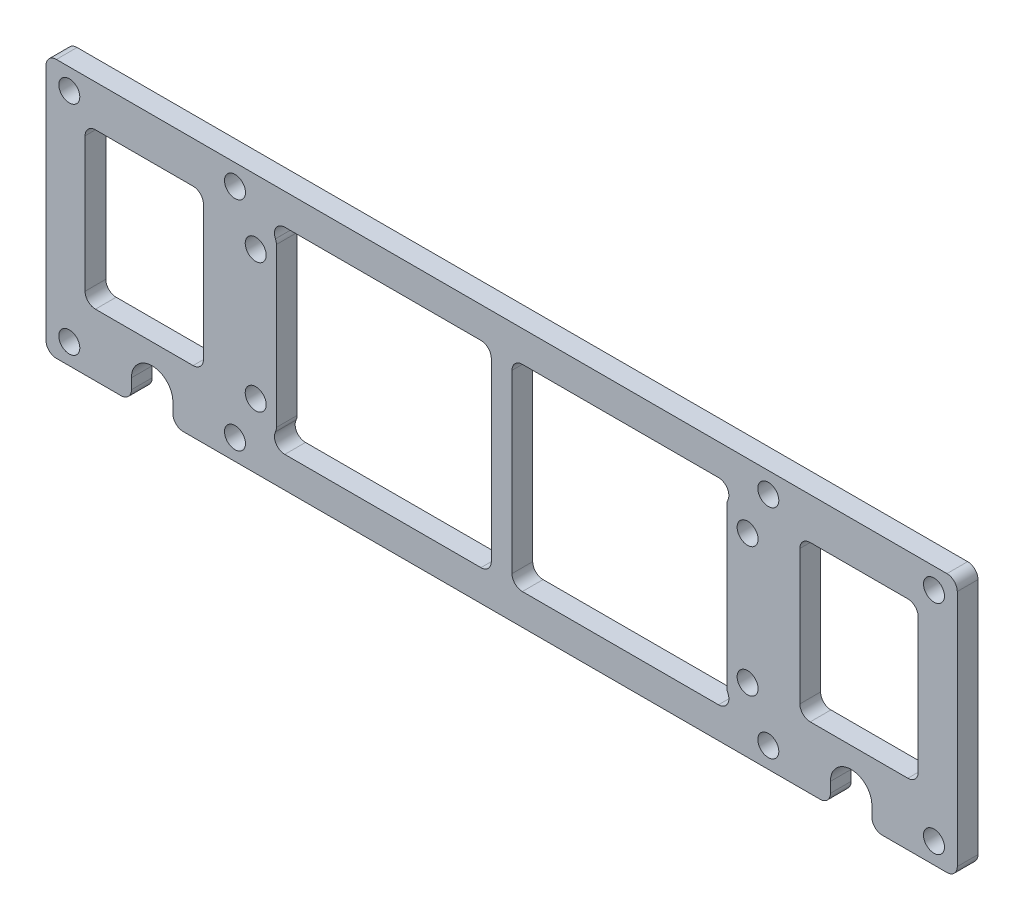
SolidWorks part; units mm, degrees
material "Thornel Mat VMA"
ref_plane "前视基准面" through (0, 0, 0) normal (0, 0, 1) x (1, 0, 0)
ref_plane "上视基准面" through (0, 0, 0) normal (0, 1, 0) x (1, 0, 0)
ref_plane "右视基准面" through (0, 0, 0) normal (1, 0, 0) x (0, 0, -1)
other "Configuration Table"
sketch "草图1" plane through (0, 0, 0) normal (0, 0, 1) x (1, 0, 0)
  line L1 (-88, -25) -> (88, -25)
  line L2 (-88, -25) -> (-88, 25)
  line L3 (-88, 25) -> (88, 25)
  line L4 (88, -25) -> (88, 25)
  line L5 (-88, -25) -> (88, 25) construction
  line L6 (-88, 25) -> (88, -25) construction
  point P0 (0, 0)
  dimension "D1" = 176
  dimension "D2" = 50
extrude "凸台-拉伸1" add sketch "草图1" along normal mid plane 4
sketch "草图2" plane through (0, 0, -2) normal (0, 0, -1) x (-1, 0, 0)
  line L0 (-88, -25) -> (-88, 25) construction
  line L1 (88, -25) -> (-88, -25) construction
  circle A4 centre (51.5, 21) radius 1.65 construction
  circle A5 centre (83.5, 21) radius 1.65 construction
  circle A6 centre (83.5, -21) radius 1.65 construction
  circle A7 centre (51.5, -21) radius 1.65 construction
  circle A8 centre (51.5, 21) radius 2.025
  circle A9 centre (51.5, -21) radius 2.025
  circle A10 centre (83.5, 21) radius 2.025
  circle A11 centre (83.5, -21) radius 2.025
  dimension "D1" = 4.05
  dimension "D2" = 3.3
  dimension "D3" = 139.5
  dimension "D4" = 171.5
  dimension "D5" = 4
  dimension "D6" = 46
extrude "切除-拉伸1" cut sketch "草图2" against normal mid plane 44
mirror "镜向1" about plane through (0, 0, 0) normal (1, 0, 0) of "切除-拉伸1"
sketch "草图3" plane through (0, 0, -2) normal (0, 0, -1) x (-1, 0, 0)
  line L0 (51.5, -21) -> (83.5, -21) construction
  line L1 (88, -25) -> (-88, -25) construction
  line L2 (67.5, -17) -> (64.0359, -19) construction
  line L3 (64.0359, -19) -> (64.0359, -23) construction
  line L4 (64.0359, -23) -> (67.5, -25) construction
  line L5 (67.5, -25) -> (70.9641, -23) construction
  line L6 (70.9641, -23) -> (70.9641, -19) construction
  line L7 (70.9641, -19) -> (67.5, -17) construction
  line L8 (63.5, -21) -> (63.5, -25)
  line L9 (63.5, -25) -> (71.5, -25)
  line L10 (71.5, -25) -> (71.5, -21)
  arc A1 (71.5, -21) -> (63.5, -21) centre (67.5, -21) ccw
extrude "切除-拉伸2" cut sketch "草图3" against normal mid plane 34
mirror "镜向2" about plane through (0, 0, 0) normal (1, 0, 0) of "切除-拉伸2"
fillet "圆角1" radius 2 8 edges at (-63.5, -25, 0) (-71.5, -25, 0) (-88, -25, 0) (-88, 25, 0) (88, 25, 0) (88, -25, 0) (63.5, -25, 0) (71.5, -25, 0)
sketch "草图4" plane through (0, 0, -2) normal (0, 0, -1) x (-1, 0, 0)
  line L0 (0, 0) -> (0, 39.7979) construction
  circle A0 centre (47.5, -12.5) radius 1.65 construction
  circle A1 centre (47.5, 12.5) radius 1.65 construction
  circle A2 centre (47.5, -12.5) radius 1.65 construction
  circle A3 centre (47.5, 12.5) radius 1.65 construction
  circle A4 centre (47.5, -12.5) radius 2.025
  circle A5 centre (47.5, 12.5) radius 2.025
  circle A7 centre (-47.5, 12.5) radius 1.65 construction
  circle A8 centre (-47.5, -12.5) radius 1.65 construction
  circle A9 centre (-47.5, 12.5) radius 2.025
  circle A10 centre (-47.5, -12.5) radius 2.025
  dimension "D1" = 4.05
extrude "切除-拉伸3" cut sketch "草图4" against normal mid plane 10
sketch "草图5" plane through (0, 0, -2) normal (0, 0, -1) x (-1, 0, 0)
  line L0 (61.5, -25) -> (-61.5, -25) construction
  line L1 (-47, -25) -> (47, -25)
  line L2 (-47, -25) -> (-47, -90)
  line L3 (-47, -90) -> (47, -90)
  line L4 (47, -25) -> (47, -90)
  line L5 (0, 0) -> (0, -90) construction
  dimension "D1" = 94
  dimension "D2" = 65
extrude "凸台-拉伸2" [suppressed] add sketch "草图5" against normal up to surface (4 mm away)
sketch "草图7" plane through (0, 0, 2) normal (0, 0, 1) x (1, 0, 0)
  line L5 (-45.0329, 19) -> (-43.5, 15.7427)
  line L6 (-43.5, 15.7427) -> (-43.5, -15.7427)
  line L7 (-43.5, -15.7427) -> (-45.0329, -19)
  line L8 (-45.0329, -19) -> (45.0329, -19)
  line L9 (0, -19) -> (0, 0) construction
  line L10 (-45.0329, 19) -> (45.0329, 19)
  line L11 (0, 0) -> (-43.5, 0) construction
  line L12 (-51.5, 21) -> (-47.5, 12.5) construction
  line L13 (-47.5, 12.5) -> (-47.5, -12.5) construction
  line L14 (-47.5, -12.5) -> (-51.5, -21) construction
  line L15 (-61.5, -25) -> (61.5, -25) construction
  line L16 (45.0329, 19) -> (43.5, 15.7427)
  line L17 (43.5, -15.7427) -> (45.0329, -19)
  line L18 (43.5, 15.7427) -> (43.5, -15.7427)
  line L19 (0, 19) -> (0, -19) construction
  line L20 (-2, 19) -> (-2, -19)
  line L21 (2, 19) -> (2, -19)
  point P23 (0, 19)
  dimension "D1" = 8
  dimension "D2" = 5
  dimension "D3" = 6
  dimension "D4" = 2
  dimension "D5" = 2
extrude "切除-拉伸5" cut sketch "草图7" against normal mid plane 31 contours L20 L10 L5 L6 L7 L8 | L10 L21 L8 L17 L18 L16
sketch "草图8" plane through (0, 0, 2) normal (0, 0, 1) x (1, 0, 0)
  line L0 (-83.5, 21) -> (-51.5, -21) construction
  line L1 (0, 0) -> (0, -25) construction
  line L2 (-80.4524, 17) -> (-57.5952, 17)
  line L3 (-80.4524, 17) -> (-80.4524, -13)
  line L4 (-80.4524, -13) -> (-57.5952, -13)
  line L5 (-57.5952, 17) -> (-57.5952, -13)
  line L6 (-61.5, -25) -> (61.5, -25) construction
  line L7 (80.4524, -13) -> (57.5952, -13)
  line L8 (57.5952, 17) -> (57.5952, -13)
  line L9 (80.4524, 17) -> (57.5952, 17)
  line L10 (80.4524, 17) -> (80.4524, -13)
  circle A0 centre (-51.5, 21) radius 2.025 construction
  arc A1 (-63.5, -21) -> (-71.5, -21) centre (-67.5, -21) ccw construction
  dimension "D1" = 4
  dimension "D2" = 8
extrude "切除-拉伸6" cut sketch "草图8" against normal mid plane 31
fillet "圆角2" radius 2 20 edges at (-45.0329, -19, 0) (-43.5, -15.7427, 0) (-43.5, 15.7427, 0) (-45.0329, 19, 0) (-2, 19, 0) (-2, -19, 0) (43.5, 15.7427, 0) (43.5, -15.7427, 0) (45.0329, -19, 0) (2, -19, 0) (2, 19, 0) (45.0329, 19, 0) (80.4524, -13, 0) (57.5952, -13, 0) (57.5952, 17, 0) (80.4524, 17, 0) (-80.4524, 17, 0) (-57.5952, 17, 0) (-80.4524, -13, 0) (-57.5952, -13, 0)
sketch "草图9" [suppressed] plane through (0, 0, -2) normal (0, 0, -1) x (-1, 0, 0)
  line L0 (0, -52) -> (0, 0) construction
  line L1 (65, -79) -> (-65, -79)
  line L2 (65, -79) -> (65, -25)
  line L3 (65, -25) -> (-65, -25)
  line L4 (-65, -79) -> (-65, -25)
  line L5 (65, -79) -> (-65, -25) construction
  line L6 (65, -25) -> (-65, -79) construction
  line L8 (61.5, -25) -> (-61.5, -25) construction
  point P0 (0, -52)
  dimension "D1" = 54
  dimension "D2" = 130
extrude "凸台-拉伸3" [suppressed] add sketch "草图9" against normal up to surface (4 mm away)
sketch "草图10" [suppressed] plane through (0, 0, -2) normal (0, 0, -1) x (-1, 0, 0)
  line L0 (-65, -79) -> (65, -79) construction
  line L1 (53, -26) -> (-53, -26)
  line L2 (53, -26) -> (53, -79)
  line L3 (53, -79) -> (-53, -79)
  line L4 (-53, -26) -> (-53, -79)
  line L5 (53, -26) -> (-53, -79) construction
  line L6 (53, -79) -> (-53, -26) construction
  line L7 (0, -52.5) -> (0, 0) construction
  point P0 (0, -52.5)
  dimension "D1" = 106
  dimension "D2" = 53
extrude "切除-拉伸7" [suppressed] cut sketch "草图10" against normal blind 10
